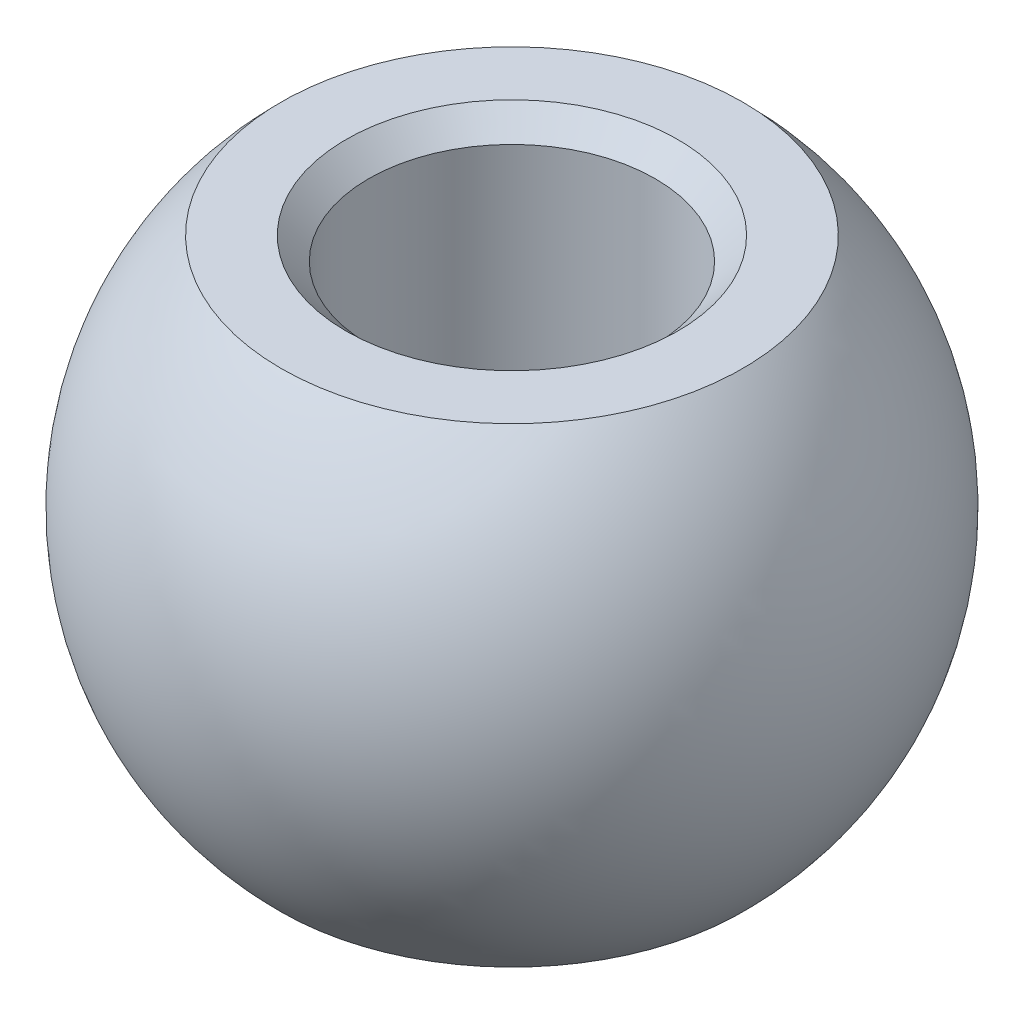
SolidWorks part; units mm, degrees
material "6061-T6 (SS)"
ref_plane "Front Plane" through (0, 0, 0) normal (0, 0, 1) x (1, 0, 0)
ref_plane "Top Plane" through (0, 0, 0) normal (0, 1, 0) x (1, 0, 0)
ref_plane "Right Plane" through (0, 0, 0) normal (1, 0, 0) x (0, 0, -1)
sketch "Sketch1" plane through (0, 0, 0) normal (0, 0, 1) x (1, 0, 0)
  line L0 (2.413, 0) -> (2.413, 7.9248)
  line L1 (2.413, 7.9248) -> (3.8862, 7.9248)
  line L2 (2.413, 0) -> (3.8862, 0)
  line L4 (0, 0) -> (0, 9.3945) construction
  arc A0 (3.8862, 7.9248) -> (3.8862, 0) centre (0.0002, 3.9624) cw
  point P9 (0, 0)
  dimension "D1" = 5.5499
  dimension "D2" = 1.4732
  dimension "D3" = 2.413
  dimension "D4" = 7.9248
revolve "Revolve1" add sketch "Sketch1" angle 360 about L4
chamfer "Chamfer1" distance 0.381 angle 45 2 edges at (0, 0, -2.413) (0, 7.9248, -2.413)
ref_plane "Plane1" through (0, 3.9624, 0) normal (0, 1, 0) x (1, 0, 0)
sketch "Sketch2" plane through (0, 3.9624, 0) normal (0, 1, 0) x (1, 0, 0)
  circle A0 centre (0, 0) radius 2.413 construction
  circle A1 centre (0, 0) radius 2.413 construction
  point P4 (0, 0)
